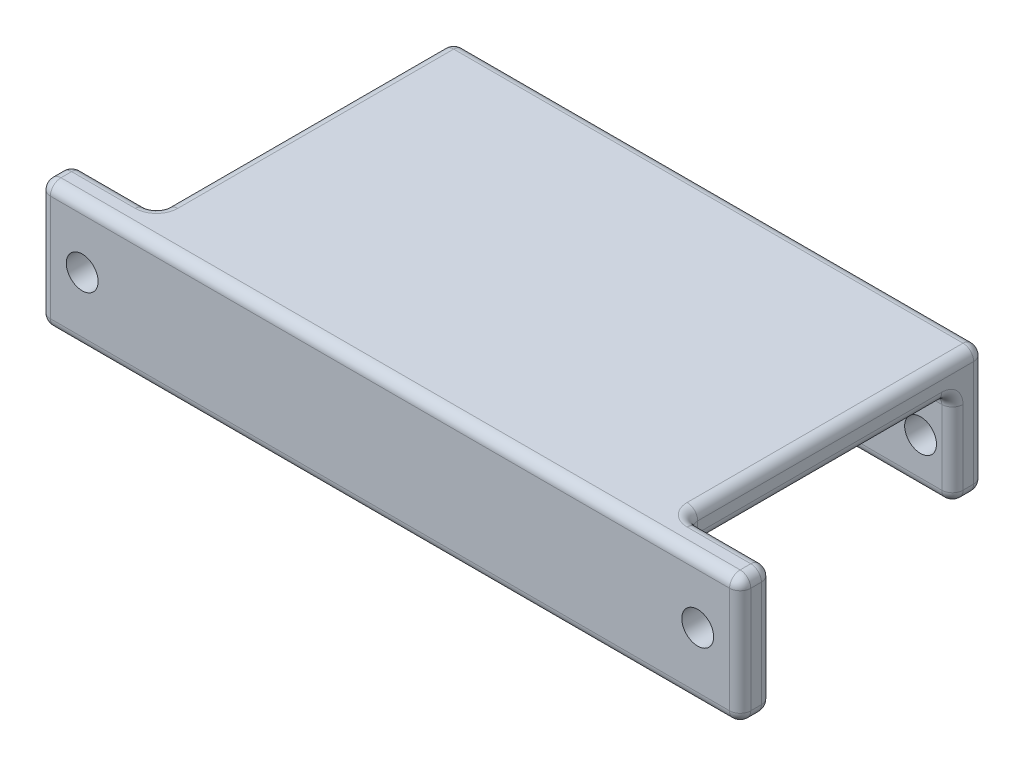
SolidWorks part; units mm, degrees
ref_plane "Piano frontale" through (0, 0, 0) normal (0, 0, 1) x (1, 0, 0)
ref_plane "Piano superiore" through (0, 0, 0) normal (0, 1, 0) x (1, 0, 0)
ref_plane "Piano destro" through (0, 0, 0) normal (1, 0, 0) x (0, 0, -1)
sketch "Schizzo1" plane through (0, 0, 0) normal (0, 0, 1) x (1, 0, 0)
  line L1 (25, -6) -> (-25, -6)
  line L2 (25, -6) -> (25, 6)
  line L3 (25, 6) -> (-25, 6)
  line L4 (-25, -6) -> (-25, 6)
  line L5 (25, -6) -> (-25, 6) construction
  line L6 (25, 6) -> (-25, -6) construction
  point P0 (0, 0)
  dimension "D1" = 12
  dimension "D2" = 50
extrude "Estrusione-Estrusione1" add sketch "Schizzo1" along normal blind 3 contours L1 L4 L3 L2
sketch "Schizzo2" plane through (0, 0, 3) normal (0, 0, 1) x (1, 0, 0)
  line L0 (25, -6) -> (25, 6) construction
  line L1 (-25, 6) -> (25, 6)
  line L2 (-25, 6) -> (-25, 3)
  line L3 (-25, 3) -> (25, 3)
  line L4 (25, 6) -> (25, 3)
  dimension "D1" = 3
extrude "Estrusione-Estrusione2" add sketch "Schizzo2" along normal blind 25
sketch "Schizzo3" plane through (0, 0, 28) normal (0, 0, 1) x (1, 0, 0)
  line L0 (0, 0) -> (0, 6) construction
  line L5 (25, 6) -> (-25, 6) construction
  line L6 (0, 6) -> (-33, 6) construction
  line L7 (33, 6) -> (-33, 6)
  line L12 (33, -6) -> (-33, -6)
  line L13 (33, -6) -> (33, 6)
  line L19 (-33, -6) -> (-33, 6)
  line L20 (33, -6) -> (-33, 6) construction
  line L21 (33, 6) -> (-33, -6) construction
  dimension "D1" = 33
extrude "Estrusione-Estrusione3" add sketch "Schizzo3" along normal blind 3
sketch "Schizzo5" plane through (0, 0, 31) normal (0, 0, 1) x (1, 0, 0)
  line L0 (0, 6) -> (0, 0.28) construction
  line L1 (33, 6) -> (-33, 6) construction
  line L4 (0, 0.28) -> (33, 0.28) construction
  line L5 (33, -6) -> (33, 6) construction
  circle A6 centre (29, 0.28) radius 1.5
  circle A7 centre (-29, 0.28) radius 1.5
  dimension "D2" = 3
  dimension "D3" = 29
  dimension "D1" = 5.72
extrude "Taglio-Estrusione1" cut sketch "Schizzo5" against normal blind 6
sketch "Schizzo6" plane through (0, 0, 0) normal (0, 0, -1) x (-1, 0, 0)
  line L0 (-25, 3) -> (25, 3) construction
  line L3 (-25, 3) -> (25, -6) construction
  line L5 (25, -6) -> (25, 6) construction
  line L6 (-25, -6) -> (25, -6) construction
  line L7 (-25, -6) -> (25, 3) construction
  line L8 (0, -1.5) -> (-25, -1.5) construction
  line L9 (-25, -6) -> (-25, 6) construction
  line L10 (0, -1.5) -> (0, -6) construction
  circle A2 centre (-22, -1.5) radius 1.5
  circle A3 centre (22, -1.5) radius 1.5
  dimension "D1" = 3
  dimension "D2" = 22
extrude "Taglio-Estrusione2" cut sketch "Schizzo6" against normal blind 6
fillet "Raccordo1" radius 1 30 edges at (-29, 6, 28) (29, 6, 28) (-25, 4.5, 28) (25, 4.5, 28) (0, 6, 31) (-33, 0, 31) (-33, -6, 29.5) (0, -6, 31) (0, -6, 28) (-33, 6, 29.5) (-33, 0, 28) (0, 3, 28) (-25, 6, 14) (-25, 3, 15.5) (-25, -6, 1.5) (-25, -1.5, 3) (33, -6, 29.5) (33, 6, 29.5) (33, 0, 31) (33, 0, 28) (25, 3, 15.5) (25, 6, 14) (25, -6, 1.5) (0, -6, 3) (25, -1.5, 3) (25, 0, 0) (0, -6, 0) (-25, 0, 0) (0, 6, 0) (0, 3, 3)
